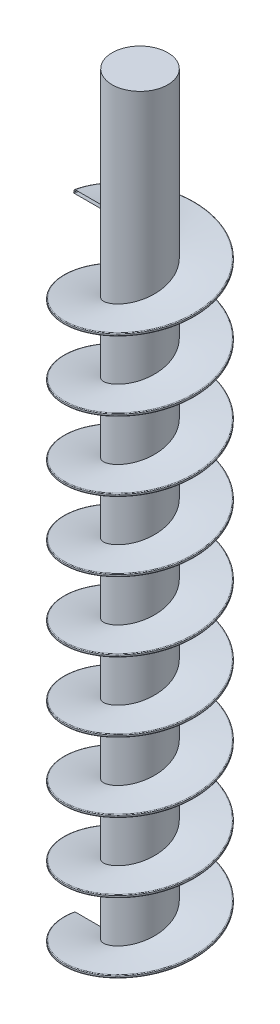
SolidWorks part; units mm, degrees
ref_plane "Front Plane" through (0, 0, 0) normal (0, 0, 1) x (1, 0, 0)
ref_plane "Top Plane" through (0, 0, 0) normal (0, 1, 0) x (1, 0, 0)
ref_plane "Right Plane" through (0, 0, 0) normal (1, 0, 0) x (0, 0, -1)
sketch "Sketch1" plane through (0, 0, 0) normal (0, 1, 0) x (1, 0, 0)
  circle A0 centre (0, 0) radius 4
  dimension "D1" = 8
extrude "Boss-Extrude1" add sketch "Sketch1" along normal blind 110
sketch "Sketch11" plane through (0, 0, 0) normal (0, -1, 0) x (1, 0, 0)
  circle A1 centre (0, 0) radius 4
  circle A2 centre (0, 0) radius 4
  dimension "D1" = 0
curve "Helix/Spiral1" pitch 10 height 90 turns 9
ref_plane "Plane1" through (-4, 0, 0) normal (0, 0.3697, 0.9292) x (1, 0, 0)
sketch "Sketch12" plane through (-4, 0, 0) normal (0, 0.3697, 0.9292) x (1, 0, 0)
  line L0 (4, 0) -> (-15.106, 0) construction
  line L1 (0.0368, 0.2) -> (-5.4, 0.2)
  line L2 (0.0368, -0.2) -> (-5.4, -0.2)
  line L3 (4, 0.2) -> (-15.106, 0.2) construction
  line L4 (4, -0.2) -> (-15.106, -0.2) construction
  line L5 (-5.5, 0.1) -> (-5.5, -0.1)
  arc A0 (-5.4, 0.2) -> (-5.5, 0.1) centre (-5.4, 0.1) ccw
  arc A1 (-5.4, -0.2) -> (-5.5, -0.1) centre (-5.4, -0.1) cw
  ellipse E1 centre (4, 0) end of major axis (8, 0) minor radius 1.4788
  ellipse E2 centre (4, 0) end of major axis (8, 0) minor radius 1.4788 (0.0368, 0.2) -> (0.0368, -0.2) ccw
  point P26 (-5.5, 0)
  dimension "D4" = 0.1
  dimension "D5" = 0.1
  dimension "D6" = 9.5
  dimension "D1" = 0.2
  dimension "D2" = 0.2
  dimension "D3" = 0
surface "Surface-Sweep2"
